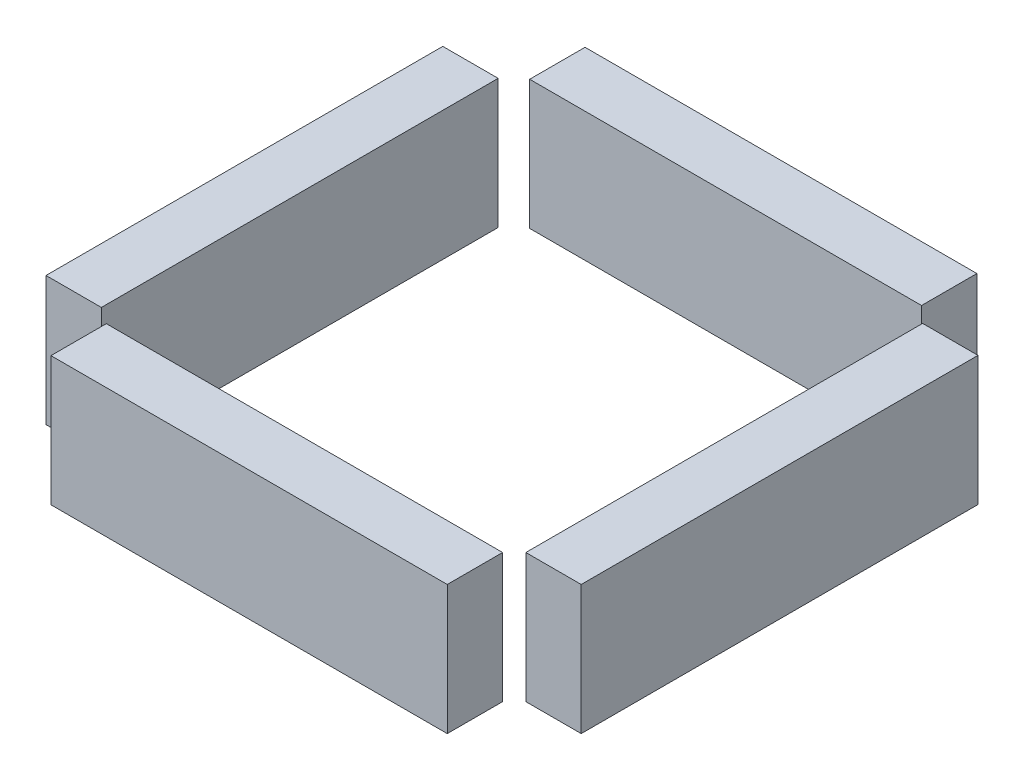
SolidWorks part; units mm, degrees
ref_plane "Front Plane" through (0, 0, 0) normal (0, 0, 1) x (1, 0, 0)
ref_plane "Top Plane" through (0, 0, 0) normal (0, 1, 0) x (1, 0, 0)
ref_plane "Right Plane" through (0, 0, 0) normal (1, 0, 0) x (0, 0, -1)
sketch "Sketch7" plane through (0, 0, -1.5875) normal (0, 1, 0) x (-1, 0, 0)
  line L1 (0, 1.5875) -> (-100, 1.5875) construction
  line L2 (0, 1.5875) -> (0, -73.4125) construction
  line L3 (0, -73.4125) -> (-100, -73.4125) construction
  line L4 (-100, 1.5875) -> (-100, -73.4125) construction
  line L6 (-37.798, -23.8026) -> (-43.798, -23.8026)
  line L7 (-37.798, -23.8026) -> (-37.798, -66.8026)
  line L8 (-37.798, -66.8026) -> (-43.798, -66.8026)
  line L12 (-43.798, -23.8026) -> (-43.798, -66.8026)
  line L17 (-89.798, -23.8026) -> (-95.798, -23.8026)
  line L18 (-89.798, -23.8026) -> (-89.798, -66.8026)
  line L19 (-89.798, -66.8026) -> (-95.798, -66.8026)
  line L20 (-95.798, -23.8026) -> (-95.798, -66.8026)
  line L21 (-45.5913, -22.545) -> (-88.5392, -22.545)
  line L22 (-45.5913, -22.545) -> (-45.5913, -16.545)
  line L23 (-45.5913, -16.545) -> (-88.5392, -16.545)
  line L24 (-88.5392, -22.545) -> (-88.5392, -16.545)
  line L25 (-45.5913, -74.4244) -> (-88.0566, -74.4244)
  line L26 (-45.5913, -74.4244) -> (-45.5913, -68.4244)
  line L27 (-45.5913, -68.4244) -> (-88.0566, -68.4244)
  line L28 (-88.0566, -74.4244) -> (-88.0566, -68.4244)
extrude "Boss-Extrude3" add sketch "Sketch7" along normal blind 14
